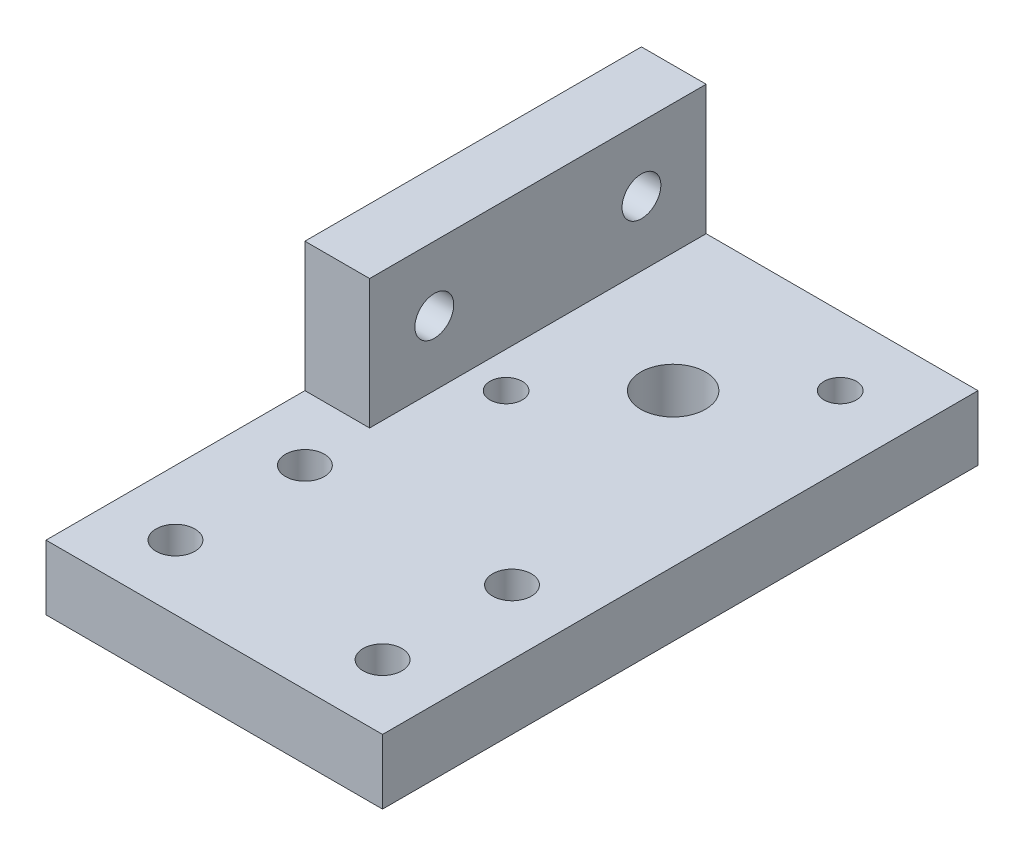
SolidWorks part; units mm, degrees
ref_plane "Front Plane" through (0, 0, 0) normal (0, 0, 1) x (1, 0, 0)
ref_plane "Top Plane" through (0, 0, 0) normal (0, 1, 0) x (1, 0, 0)
ref_plane "Right Plane" through (0, 0, 0) normal (1, 0, 0) x (0, 0, -1)
sketch "Sketch1" plane through (0, 0, 0) normal (0, 1, 0) x (1, 0, 0)
  line L0 (0, 0) -> (52, 0)
  line L1 (52, 0) -> (52, 92)
  line L2 (52, 92) -> (0, 92)
  line L3 (0, 92) -> (0, 0)
  dimension "D1" = 52
  dimension "D2" = 92
extrude "Boss-Extrude1" add sketch "Sketch1" along normal blind 10
sketch "Sketch2" plane through (0, 10, 0) normal (0, 1, 0) x (1, 0, 0)
  line L1 (0, 92) -> (10, 92)
  line L2 (0, 92) -> (0, 40)
  line L3 (0, 40) -> (10, 40)
  line L4 (10, 92) -> (10, 40)
  dimension "D1" = 52
  dimension "D2" = 10
extrude "Boss-Extrude2" add sketch "Sketch2" along normal blind 20
sketch "Sketch3" plane through (0, 10, 0) normal (0, 1, 0) x (1, 0, 0)
  line L0 (0, 40) -> (0, 0) construction
  line L1 (0, 0) -> (52, 0) construction
  line L2 (52, 0) -> (52, 92) construction
  line L3 (52, 92) -> (10, 92) construction
  line L4 (28.45, 68.45) -> (52, 92) construction
  line L5 (28.45, 68.45) -> (11.1045, 51.1045) construction
  circle A0 centre (42, 30) radius 3
  circle A1 centre (10, 30) radius 3
  circle A2 centre (42, 10) radius 3
  circle A3 centre (10, 10) radius 3
  circle A4 centre (28.45, 68.45) radius 5
  circle A5 centre (41.3547, 81.3547) radius 2.5
  circle A6 centre (15.5453, 55.5453) radius 2.5
  point P24 (15.3352, 55.3352)
  dimension "D1" = 6
  dimension "D8" = 10
  dimension "D10" = 5
  dimension "D2" = 20
  dimension "D3" = 32
  dimension "D4" = 10
  dimension "D5" = 10
  dimension "D6" = 23.55
  dimension "D7" = 23.55
  dimension "D9" = 18.25
  dimension "D11" = 18.25
extrude "Cut-Extrude1" cut sketch "Sketch3" against normal up to next
sketch "Sketch4" plane through (10, 0, 0) normal (1, 0, 0) x (0, 0, -1)
  line L2 (40, 10) -> (92, 10) construction
  line L3 (92, 30) -> (92, 10) construction
  line L4 (40, 30) -> (40, 10) construction
  circle A2 centre (50, 20.005) radius 3
  circle A3 centre (82, 20.005) radius 3
  point P4 (0, 0)
  point P9 (0, 0)
  point P10 (0, 0)
  point P11 (0, 0)
  dimension "D1" = 10
  dimension "D3" = 6
  dimension "D2" = 10
  dimension "D5" = 10.005
extrude "Cut-Extrude2" cut sketch "Sketch4" against normal up to next
